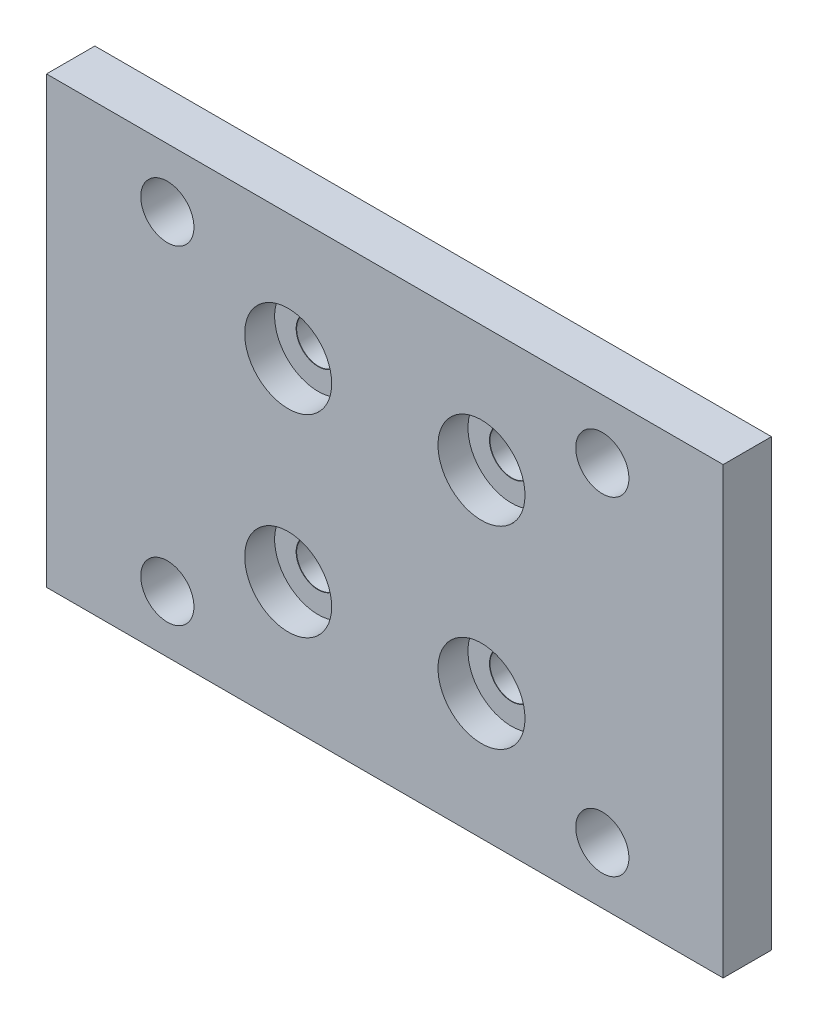
SolidWorks part; units mm, degrees
ref_plane "Plan de face" through (0, 0, 0) normal (0, 0, 1) x (1, 0, 0)
ref_plane "Plan de dessus" through (0, 0, 0) normal (0, 1, 0) x (1, 0, 0)
ref_plane "Plan de droite" through (0, 0, 0) normal (1, 0, 0) x (0, 0, -1)
sketch "Esquisse1" plane through (0, 0, 0) normal (0, 0, 1) x (1, 0, 0)
  line L1 (-35, -23) -> (35, -23)
  line L2 (-35, -23) -> (-35, 23)
  line L3 (-35, 23) -> (35, 23)
  line L4 (35, -23) -> (35, 23)
  line L5 (-35, -23) -> (35, 23) construction
  line L6 (-35, 23) -> (35, -23) construction
  point P0 (0, 0)
  dimension "D1" = 70
  dimension "D2" = 46
extrude "Boss.-Extru.1" add sketch "Esquisse1" along normal blind 5
hole_wizard "Dégagement M51" positions "Esquisse3" profile "Esquisse2" hole size "M5" standard "JIS" end condition through all
sketch "Esquisse3" plane through (0, 0, 5) normal (0, 0, 1) x (1, 0, 0)
  point P0 (22.5, -17.1164)
  point P3 (22.5, 16.8836)
  point P5 (-22.5, 16.8836)
  point P7 (-22.5, -17.1164)
sketch "Esquisse2" plane through (22.5, -17.1164, 5) normal (1, 0, 0) x (0, -1, 0)
  line L0 (0, 0) -> (0, 5)
  line L1 (0, 5) -> (2.75, 5)
  line L2 (2.75, 5) -> (2.75, 0)
  line L5 (2.75, 0) -> (0, 0)
  line L11 (0, -6.35) -> (0, 107.95) construction
  dimension "Diamètre du perçage jusqu'au prochain" = 5.5
  dimension "Profondeur du perçage jusqu'au prochain" = 5
hole_wizard "Dégagement M41" positions "Esquisse5" profile "Esquisse4" hole size "M4" standard "JIS" end condition through all
sketch "Esquisse5" plane through (0, 0, 0) normal (0, 0, -1) x (-1, 0, 0)
  point P0 (10, -10)
  point P2 (-10, -10)
  point P3 (-10, 10)
  point P5 (10, 10)
sketch "Esquisse4" plane through (-10, -10, 0) normal (1, 0, 0) x (0, 1, 0)
  line L0 (0, 0) -> (0, 5)
  line L1 (0, 5) -> (2.25, 5)
  line L2 (2.25, 5) -> (2.25, 0)
  line L5 (2.25, 0) -> (0, 0)
  line L11 (0, -6.35) -> (0, 107.95) construction
  dimension "Diamètre du perçage jusqu'au prochain" = 4.5
  dimension "Profondeur du perçage jusqu'au prochain" = 5
hole_wizard "Chambrage pour vis à tête ronde bombée M41" positions "Esquisse7" profile "Esquisse6" counterbore size "M4" standard "Ansi Metric" end condition through all
sketch "Esquisse7" plane through (0, 0, 5) normal (0, 0, 1) x (1, 0, 0)
  point P0 (-10, -10)
  point P2 (-10, 10)
  point P4 (10, 10)
  point P6 (10, -10)
sketch "Esquisse6" plane through (-10, -10, 5) normal (1, 0, 0) x (0, -1, 0)
  line L0 (0, 0) -> (0, 5)
  line L1 (0, 5) -> (2.25, 5)
  line L2 (2.25, 3.125) -> (2.25, 5)
  line L3 (2.25, 3.125) -> (2.275, 3.1)
  line L4 (2.275, 3.1) -> (4.5, 3.1)
  line L5 (4.5, 3.1) -> (4.5, 0)
  line L7 (0, 0) -> (4.5, 0)
  line L9 (-2.25, 3.125) -> (-2.275, 3.1) construction
  line L11 (0, -6.35) -> (0, 107.95) construction
  dimension "Diamètre du perçage jusqu'au prochain" = 4.5
  dimension "Profondeur du perçage jusqu'au prochain" = 5
  dimension "Diamètre du chambrage" = 9
  dimension "Profondeur du chambrage" = 3.1
  dimension "Diamètre du fraisage milieu" = 4.55
  dimension "Angle du fraisage milieu" = 90
